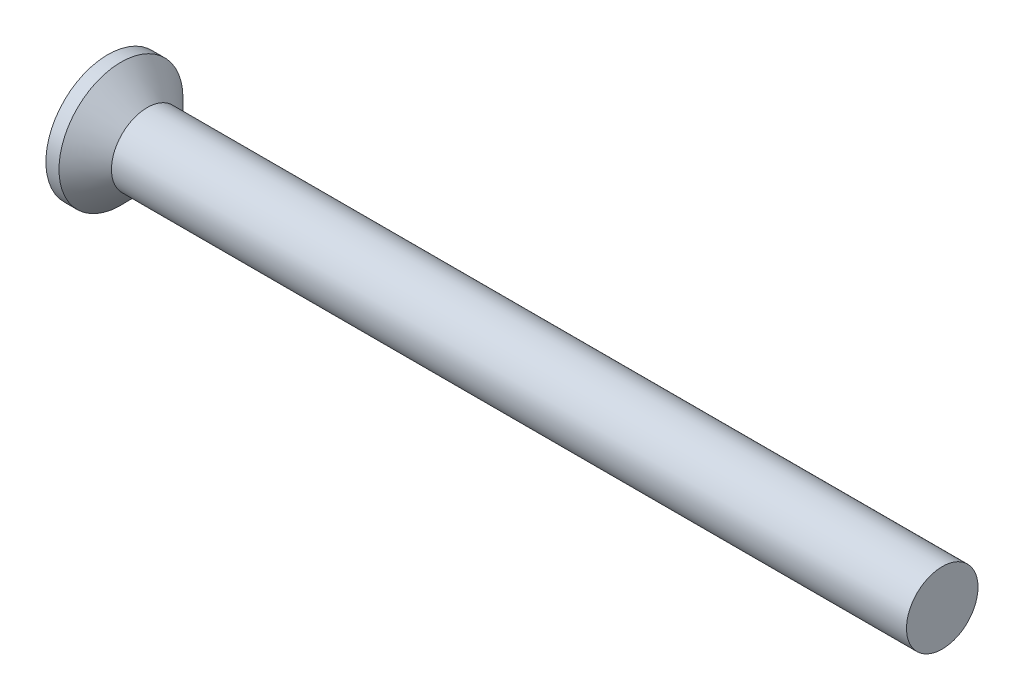
SolidWorks part; units mm, degrees
ref_plane "Front" through (0, 0, 0) normal (0, 0, 1) x (1, 0, 0)
ref_plane "Top" through (0, 0, 0) normal (0, 1, 0) x (1, 0, 0)
ref_plane "Right" through (0, 0, 0) normal (1, 0, 0) x (0, 0, -1)
sketch "Sketch1" plane through (0, 0, 0) normal (0, 0, 1) x (1, 0, 0)
  line L0 (35, 1.5) -> (2.65, 1.5)
  line L1 (2.65, 1.5) -> (1.65, 1.5)
  line L2 (1.65, 1.5) -> (0.55, 2.6)
  line L3 (0.55, 2.6) -> (0, 2.6)
  line L4 (35, 1.5) -> (35, 0)
  line L5 (4.5158, 0) -> (-89.8219, 0) construction
  line L6 (35, 0) -> (0, 0)
  line L7 (0, 2.6) -> (0, 0)
  dimension "d" = 3
  dimension "D1" = 45
  dimension "dk" = 5.2
  dimension "k" = 1.65
  dimension "l" = 35
  dimension "a" = 1
revolve "Base" add sketch "Sketch1" angle 360 about L5
cosmetic thread "ThreadCosmetic1" [suppressed] parameters "bb"=28.35, "THD_MINOR"=2.459
sketch "Sketch6" plane through (0, 0, 0) normal (1, 0, 0) x (0, 0, -1)
  line L0 (-1.9271, 0) -> (2.0512, 0) construction
  line L1 (0, 1.8651) -> (0, -2.0207) construction
  line L2 (0.32, 0.32) -> (0.32, 1.6)
  line L3 (0.32, 1.6) -> (-0.32, 1.6)
  line L4 (-0.32, 0.32) -> (-0.32, 1.6)
  line L5 (0.32, 0.32) -> (1.6, 0.32)
  line L6 (1.6, 0.32) -> (1.6, -0.32)
  line L7 (-1.6, 0.32) -> (-1.6, -0.32)
  line L8 (-0.32, 0.32) -> (-1.6, 0.32)
  line L9 (-0.32, -0.32) -> (-1.6, -0.32)
  line L10 (0.32, -0.32) -> (1.6, -0.32)
  line L11 (-0.32, -0.32) -> (-0.32, -1.6)
  line L12 (0.32, -1.6) -> (-0.32, -1.6)
  line L13 (0.32, -0.32) -> (0.32, -1.6)
  point P16 (-1.6, 0)
  point P17 (1.6, 0)
extrude "CrossRecess" cut sketch "Sketch6" along normal blind 0.825
draft "Draft9" type of draft neutral plane draft angle 30 faces to draft 4 face at (0.4125, 1.6, 0) face at (0.4125, 0, 1.6) face at (0.4125, -1.6, 0) face at (0.4125, 0, -1.6) neutral plane through (0, 2.6, 0) neutral plane normal (-1, 0, 0) parameters "D1"=30
fillet "Fillet5" radius 0.3 4 edges at (0.4125, -0.32, -0.32) (0.4125, 0.32, -0.32) (0.4125, 0.32, 0.32) (0.4125, -0.32, 0.32)
sketch "Sketch7" plane through (0, 0, 0) normal (1, 0, 0) x (0, 0, -1)
  line L0 (-2.0126, 0) -> (1.9757, 0) construction
  line L1 (0, 1.9314) -> (0, -2.0126) construction
  line L2 (0, 0) -> (1.5555, 1.5555) construction
  line L3 (0, 0.4782) -> (1.1314, 1.1314)
  line L4 (-1.5402, 1.5402) -> (0, 0) construction
  line L5 (0.4782, 0) -> (1.1314, 1.1314)
  line L6 (0, -0.4782) -> (1.1314, -1.1314)
  line L7 (0.4782, 0) -> (1.1314, -1.1314)
  line L8 (-0.4782, 0) -> (-1.1314, -1.1314)
  line L9 (0, -0.4782) -> (-1.1314, -1.1314)
  line L10 (-0.4782, 0) -> (-1.1314, 1.1314)
  line L11 (0, 0.4782) -> (-1.1314, 1.1314)
  dimension "D3" = 15
  dimension "m" = 3.2
extrude "Cut-Extrude3" [suppressed] cut sketch "Sketch7" along normal blind 10 draft 20
sketch "Sketch8" plane through (0, 0, 0) normal (0, 0, 1) x (1, 0, 0)
  line L0 (10, 1.7705) -> (8.75, 1.5)
  line L1 (8.75, 1.5) -> (1.65, 1.5)
  line L3 (35, -1.5) -> (35, 1.5) construction
  line L6 (1.65, 1.5) -> (1.65, 6.5)
  line L7 (1.65, 6.5) -> (10, 6.5)
  line L8 (10, 6.5) -> (10, 1.7705)
  line L9 (62.4753, 0.2705) -> (52.9594, 0.2705) construction
  dimension "D1" = 5
  dimension "x" = 1.25
  dimension "d" = 3
  dimension "THD_MINOR" = 2.459
  dimension "b" = 25
sketch "Sketch9" plane through (0, 0, 0) normal (0, 0, 1) x (1, 0, 0)
  line L0 (35, 1.2657) -> (35.1353, 1.5)
  line L1 (35.1353, 1.5) -> (35.1353, 1.7705)
  line L2 (35.1353, 1.7705) -> (34.8648, 1.7705)
  line L3 (34.8648, 1.7705) -> (34.8648, 1.5)
  line L4 (34.8648, 1.5) -> (35, 1.2657)
  line L5 (0, 0) -> (73.843, 0) construction
  line L6 (35, -1.5) -> (35, 1.5) construction
  dimension "D1" = 3
  dimension "D2" = 0.2705
revolve "Cut-Revolve10" [suppressed] cut sketch "Sketch9" angle 360 about L5
pattern_linear "LPattern10" [suppressed] count 87 spacing 0.3246 along (1, 0, 0)
equation "\"D1@Sketch6\" = \"m@Sketch6\" / 5"
equation "\"D1@CrossRecess\" = \"k@Sketch1\" / 2"
equation "\"D1@Sketch9\" = \"d@Sketch1\""
equation "\"D2@Sketch9\" =  ( \"d@Sketch1\" - \"THD_MINOR@ThreadCosmetic1\" )  / 2"
equation "\"D3@LPattern10\" = \"D2@Sketch9\" * 1.2"
equation "\"D1@LPattern10\" = \"bb@ThreadCosmetic1\" / \"D3@LPattern10\" "
